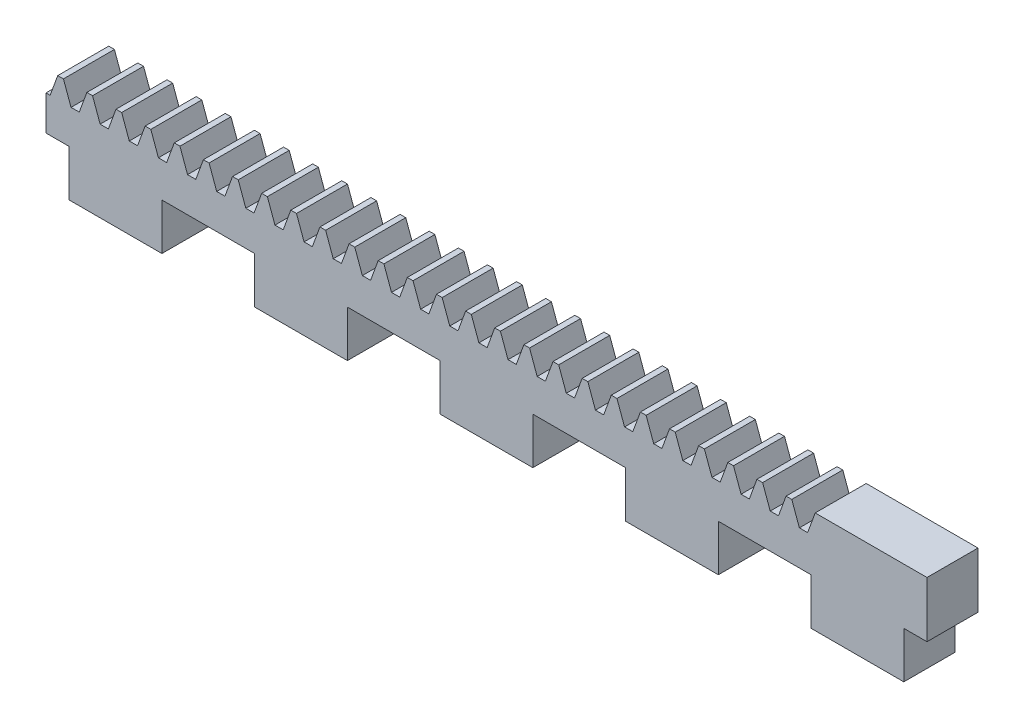
SolidWorks part; units mm, degrees
extrude "Blank" add sketch "BlankSke" against normal blind 5.5
sketch "BlankSke" plane through (0, 0, 0) normal (0, 0, 1) x (1, 0, 0)
  line L1 (0, 0) -> (95, 0)
  line L2 (0, 0) -> (0, 11)
  line L3 (0, 11) -> (95, 11)
  line L4 (95, 0) -> (95, 11)
  dimension "Length" = 95
  dimension "Blank_height" = 11
ref_plane "Plane1" through (0, 0, 0) normal (0, 0, 1) x (1, 0, 0)
ref_plane "Plane2" through (0, 0, 0) normal (0, 1, 0) x (1, 0, 0)
ref_plane "Plane3" through (0, 0, 0) normal (1, 0, 0) x (0, 0, -1)
sketch "HoldingSke" plane through (0, 0, 0) normal (0, 1, 0) x (1, 0, 0)
  line L0 (0, 0) -> (0.1392, 0.9903)
  line L1 (-15, 0) -> (100, 0) construction
  line L2 (0, 0) -> (-2.1039, 2.3779)
  line L3 (0, 0) -> (-11.863, 4.5341)
  line L4 (0, 0) -> (7.3238, 4.5764)
  line L5 (0, 0) -> (-23.7986, -8.8762)
  line L6 (0, 0) -> (-10.5278, -7.1032)
  line L9 (-71.009, 38.7566) -> (18.2618, 71.2485)
  line L10 (-76.2, 3.3779) -> (-66.2, 3.3779)
  line L11 (0, 0) -> (-5.5, 0)
  line L12 (-76.2, 101.6) -> (-76.162, 101.6)
  line L13 (24.9733, 27.94) -> (52.9518, 28.4284)
  line L14 (24.9733, 27.94) -> (24.9743, 27.94)
  line L15 (24.9733, 27.94) -> (100.4006, 29.5858)
  circle A0 centre (0, 0) radius 19.05
  circle A1 centre (0, 0) radius 5
  circle A2 centre (0, 0) radius 12.7
  dimension "MPH" = 10
  dimension "Diameter" = 38.1
  dimension "Num_teeth" = 32
  dimension "Pitch" = 1
  dimension "Show_teeth" = 998
  dimension "Thickness" = 12.7
  dimension "Ap" = 20
  dimension "Pitch_height" = 10
  dimension "Width" = 5.5
  dimension "Backlash" = 0.038
  dimension "Addendum_fac" = 1
  dimension "Dedendum_fac" = 1.25
  dimension "Clearance_fac" = 0.25
  dimension "Dedendum_add" = 0.001
  dimension "Length" = 95
  dimension "Module" = 1
sketch "TooCutSkeIll" plane through (0, 0, 0) normal (0, 0, 1) x (1, 0, 0)
  line L0 (-1.2538, 10.9737) -> (-0.5045, 8.9152)
  line L1 (-0.2687, 8.75) -> (0.2687, 8.75)
  line L2 (0.5045, 8.9152) -> (1.2538, 10.9737)
  line L3 (95, 11) -> (0, 11) construction
  line L4 (0, 0) -> (0, 64.897) construction
  line L5 (-13.208, 10) -> (12.954, 10) construction
  line L6 (0, 0) -> (95, 0) construction
  line L7 (0.8994, 10) -> (0.8994, 48.7463) construction
  line L8 (-0.8994, 10) -> (-0.8994, 48.7463) construction
  line L9 (1.2914, 11) -> (1.2914, 11.0254)
  line L10 (-1.2914, 11) -> (-1.2914, 11.0254)
  line L11 (-1.2914, 11.0254) -> (1.2914, 11.0254)
  arc A0 (0.2687, 8.75) -> (0.5045, 8.9152) centre (0.2687, 9.001) ccw
  arc A1 (-0.5045, 8.9152) -> (-0.2687, 8.75) centre (-0.2687, 9.001) ccw
  arc A2 (1.2914, 11) -> (1.2538, 10.9737) centre (1.2914, 10.96) ccw
  arc A3 (-1.2538, 10.9737) -> (-1.2914, 11) centre (-1.2914, 10.96) ccw
  dimension "Pitch_height" = 10
  dimension "Addendum_plus" = 1.0254
  dimension "Pressure_angle" = 20
  dimension "Gap_width" = 1.7988
  dimension "Dedendum" = 1.25
extrude "ToothCutIll" [suppressed] cut sketch "TooCutSkeIll" against normal through all
sketch "TooCutSkeSim" plane through (0, 0, 0) normal (0, 0, 1) x (1, 0, 0)
  line L0 (0.4444, 8.75) -> (-0.4444, 8.75)
  line L1 (1.2726, 11.0254) -> (0.4444, 8.75)
  line L2 (0, 17.4625) -> (0, 53.467) construction
  line L3 (1.2726, 11.0254) -> (-1.2726, 11.0254)
  line L6 (-1.2726, 11.0254) -> (-0.4444, 8.75)
  line L9 (-0.8994, 10) -> (0.8994, 10) construction
  line L10 (0, 0) -> (95, 0) construction
  line L11 (0.8994, 10) -> (0.8994, 53.467) construction
  line L12 (-0.8994, 10) -> (-0.8994, 53.467) construction
  dimension "Pitch_height" = 10
  dimension "Addendum_plus" = 1.0254
  dimension "Pressure_angle" = 20
  dimension "Gap_width" = 1.7988
  dimension "Dedendum" = 1.25
extrude "ToothCutSim" cut sketch "TooCutSkeSim" against normal through all
pattern_linear "TeethCuts" count 27 spacing 3.1416 along (1, 0, 0) of "ToothCutIll", "ToothCutSim"
sketch "ｽｹｯﾁ1" plane through (0, 0, -5.5) normal (0, 0, -1) x (-1, 0, 0)
  line L0 (-102.5, 0) -> (-102.5, 5)
  line L1 (-102.5, 0) -> (-92.5, 0)
  line L6 (0, 0) -> (-95, 0) construction
  line L7 (-2.5, 0) -> (7.5, 0)
  line L8 (-2.5, 0) -> (-2.5, 5)
  line L9 (-2.5, 5) -> (7.5, 5)
  line L10 (7.5, 0) -> (7.5, 5)
  line L11 (0, 8.75) -> (0, 0) construction
  line L12 (-22.5, 0) -> (-22.5, 5)
  line L13 (-22.5, 0) -> (-12.5, 0)
  line L14 (-12.5, 0) -> (-12.5, 5)
  line L15 (-22.5, 5) -> (-12.5, 5)
  line L16 (-42.5, 0) -> (-42.5, 5)
  line L17 (-42.5, 0) -> (-32.5, 0)
  line L18 (-32.5, 0) -> (-32.5, 5)
  line L19 (-42.5, 5) -> (-32.5, 5)
  line L20 (-62.5, 0) -> (-62.5, 5)
  line L21 (-62.5, 0) -> (-52.5, 0)
  line L22 (-52.5, 0) -> (-52.5, 5)
  line L23 (-62.5, 5) -> (-52.5, 5)
  line L24 (-82.5, 0) -> (-82.5, 5)
  line L25 (-82.5, 0) -> (-72.5, 0)
  line L26 (-72.5, 0) -> (-72.5, 5)
  line L27 (-82.5, 5) -> (-72.5, 5)
  line L28 (-92.5, 0) -> (-92.5, 5)
  line L29 (-102.5, 5) -> (-92.5, 5)
  dimension "D1" = 10
  dimension "D2" = 5
  dimension "D3" = 2.5
  dimension "D4" = 6
extrude "ｶｯﾄ - 押し出し1" cut sketch "ｽｹｯﾁ1" against normal through all
equation "' \"Module@HoldingSke\" = 6.35"
equation "' \"Num_teeth@HoldingSke\" = 12"
equation "' \"Ap@HoldingSke\" =  20"
equation "' \"Ap@HoldingSke\" = 20"
equation "' \"Width@HoldingSke\" = 0.25 * 25.4"
equation "' \"Show_teeth@HoldingSke\" = 500"
equation "' \"Backlash@HoldingSke\" = 0.009 * 25.4"
equation "' \"Addendum_fac@HoldingSke\" = 1.0"
equation "' \"Dedendum_fac@HoldingSke\" = 1.25"
equation "' \"Dedendum_add@HoldingSke\" = 0.00005 * 25.4"
equation "' \"Clearance_fac@HoldingSke\" = 0.25"
equation "' \"Pitch_height@HoldingSke\" = 1 * 25.4"
equation "' \"Length@HoldingSke\" = 4.71 * 25.4"
equation "\"Pitch@HoldingSke\" = 1 / \"Module@HoldingSke\""
equation "\"MPH@HoldingSke\" = \"Dedendum_fac@HoldingSke\" / \"Pitch@HoldingSke\" + 2 * \"Dedendum_add@HoldingSke\" + 0.002 * 25.4"
equation "\"MPH@HoldingSke\" = ((sgn( \"MPH@HoldingSke\" - \"Pitch_height@HoldingSke\")+1)*( \"MPH@HoldingSke\" - \"Pitch_height@HoldingSke\"))/2 + \"Pitch_height@HoldingSke\""
equation "\"Blank_height@BlankSke\" = \"Pitch_height@HoldingSke\" + \"Addendum_fac@HoldingSke\"  / \"Pitch@HoldingSke\" "
equation "\"Length@BlankSke\" =  \"Length@HoldingSke\""
equation "\"Face_width@Blank\" = \"Width@HoldingSke\""
equation "\"Pressure_angle@TooCutSkeIll\" = \"Ap@HoldingSke\""
equation "\"Addendum_plus@TooCutSkeIll\" =  \"Addendum_fac@HoldingSke\"  / \"Pitch@HoldingSke\" + 0.001 *25.4"
equation "\"Dedendum@TooCutSkeIll\" = \"Dedendum_fac@HoldingSke\"  / \"Pitch@HoldingSke\""
equation "\"Pitch_height@TooCutSkeIll\" =  \"MPH@HoldingSke\""
equation "\"Gap_width@TooCutSkeIll\" = 3.14159265 / 2 / \"Pitch@HoldingSke\" + 6 * \"Backlash@HoldingSke\""
equation "\"Pressure_angle@TooCutSkeSim\" = \"Ap@HoldingSke\""
equation "\"Addendum_plus@TooCutSkeSim\" =  \"Addendum_fac@HoldingSke\"  / \"Pitch@HoldingSke\" + 0.001 * 25.4"
equation "\"Dedendum@TooCutSkeSim\" = \"Dedendum_fac@HoldingSke\"  / \"Pitch@HoldingSke\""
equation "\"Pitch_height@TooCutSkeSim\" =  \"MPH@HoldingSke\""
equation "\"Gap_width@TooCutSkeSim\" = 3.14159265 / 2 / \"Pitch@HoldingSke\" + 6 * \"Backlash@HoldingSke\""
equation "\"Root_fillet@TooCutSkeIll\" = \"Clearance_fac@HoldingSke\" / \"Pitch@HoldingSke\" + \"Dedendum_add@HoldingSke\""
equation "\"Break_rad@TooCutSkeIll\" = 0.02 / \"Pitch@HoldingSke\" * 2"
equation "\"Linear_pitch@TeethCuts\" = 3.14159265 / \"Pitch@HoldingSke\""
equation "\"Num_teeth@HoldingSke\" = int( ( \"Length@HoldingSke\" + 0 ) / (3.14159265 / \"Pitch@HoldingSke\")) + 0.9999  + 1"
equation " \"Num_teeth@TeethCuts\" = int( \"Show_teeth@HoldingSke\" ) + 1"
equation " \"Num_teeth@TeethCuts\" = ((sgn( \"Num_teeth@TeethCuts\" - \"Num_teeth@HoldingSke\" )-1)*( \"Num_teeth@TeethCuts\" - \"Num_teeth@HoldingSke\" ))/-2+ \"Num_teeth@HoldingSke\""
equation " \"Num_teeth@TeethCuts\" = ((sgn( \"Num_teeth@TeethCuts\" - 2.0)+1)*( \"Num_teeth@TeethCuts\" - 2.0))/2 +2.0"
